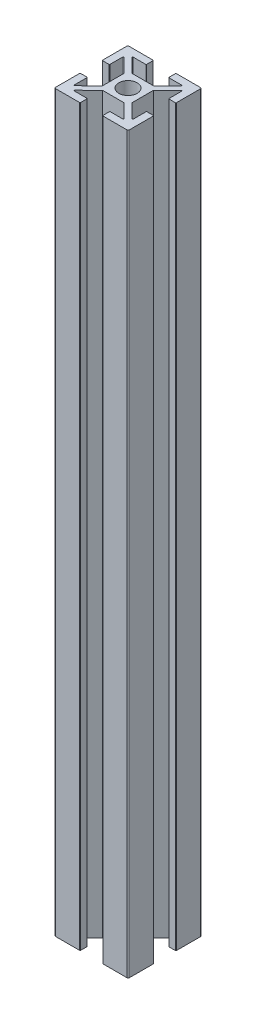
SolidWorks part; units mm, degrees
ref_plane "Front Plane" through (0, 0, 0) normal (0, 0, 1) x (1, 0, 0)
ref_plane "Top Plane" through (0, 0, 0) normal (0, 1, 0) x (1, 0, 0)
ref_plane "Right Plane" through (0, 0, 0) normal (1, 0, 0) x (0, 0, -1)
sketch "Sketch1" plane through (0, 0, 0) normal (0, 1, 0) x (1, 0, 0)
  line L0 (-9.8963, 3) -> (-8.1963, 3)
  line L3 (-3.1963, 10) -> (-9.6963, 10)
  line L4 (-10.0463, 3.15) -> (-10.0463, 9.65)
  line L7 (2.9332, 4) -> (-2.9332, 4)
  line L8 (-4, -2.9454) -> (-4, 2.9454)
  line L9 (-8.0463, 3.15) -> (-8.0463, 6.5862)
  line L10 (-6.6144, 8) -> (-3.1963, 8)
  line L11 (-3.0463, 8.15) -> (-3.0463, 9.85)
  line L12 (-8.0463, 8) -> (-4, 4) construction
  line L13 (-7.7908, 6.6929) -> (-4, 2.9454)
  line L14 (-6.7198, 7.7433) -> (-2.9332, 4)
  line L15 (8.0463, 8) -> (4, 4) construction
  line L22 (0, 0) -> (0, 11.6886) construction
  line L25 (0, 0) -> (-14.9841, 0) construction
  line L27 (6.7198, 7.7433) -> (2.9332, 4)
  line L28 (7.7908, 6.6929) -> (4, 2.9454)
  line L46 (3.0463, 8.15) -> (3.0463, 9.85)
  line L47 (6.6144, 8) -> (3.1963, 8)
  line L48 (8.0463, 3.15) -> (8.0463, 6.5862)
  line L49 (4, -2.9454) -> (4, 2.9454)
  line L50 (10.0463, 3.15) -> (10.0463, 9.65)
  line L51 (3.1963, 10) -> (9.6963, 10)
  line L52 (9.8963, 3) -> (8.1963, 3)
  line L53 (8.0463, -8) -> (4, -4) construction
  line L54 (-8.0463, -8) -> (-4, -4) construction
  line L55 (9.8963, -3) -> (8.1963, -3)
  line L56 (3.1963, -10) -> (9.6963, -10)
  line L57 (10.0463, -3.15) -> (10.0463, -9.65)
  line L58 (8.0463, -3.15) -> (8.0463, -6.5862)
  line L59 (6.6144, -8) -> (3.1963, -8)
  line L60 (3.0463, -8.15) -> (3.0463, -9.85)
  line L61 (7.7908, -6.6929) -> (4, -2.9454)
  line L62 (6.7198, -7.7433) -> (2.9332, -4)
  line L63 (-6.7198, -7.7433) -> (-2.9332, -4)
  line L64 (-7.7908, -6.6929) -> (-4, -2.9454)
  line L65 (-3.0463, -8.15) -> (-3.0463, -9.85)
  line L66 (-6.6144, -8) -> (-3.1963, -8)
  line L67 (-8.0463, -3.15) -> (-8.0463, -6.5862)
  line L68 (2.9332, -4) -> (-2.9332, -4)
  line L69 (-10.0463, -3.15) -> (-10.0463, -9.65)
  line L70 (-3.1963, -10) -> (-9.6963, -10)
  line L71 (-9.8963, -3) -> (-8.1963, -3)
  circle A0 centre (0, 0) radius 2.5
  arc A1 (-10.0463, 9.65) -> (-9.6963, 10) centre (-9.6963, 9.65) cw
  arc A2 (-9.8963, 3) -> (-10.0463, 3.15) centre (-9.8963, 3.15) cw
  arc A3 (-8.1963, 3) -> (-8.0463, 3.15) centre (-8.1963, 3.15) ccw
  arc A4 (-3.1963, 10) -> (-3.0463, 9.85) centre (-3.1963, 9.85) cw
  arc A5 (-3.1963, 8) -> (-3.0463, 8.15) centre (-3.1963, 8.15) ccw
  arc A6 (-6.7198, 7.7433) -> (-6.6144, 8) centre (-6.6144, 7.85) cw
  arc A7 (-7.7908, 6.6929) -> (-8.0463, 6.5862) centre (-7.8963, 6.5862) ccw
  arc A8 (7.7908, 6.6929) -> (8.0463, 6.5862) centre (7.8963, 6.5862) cw
  arc A9 (6.7198, 7.7433) -> (6.6144, 8) centre (6.6144, 7.85) ccw
  arc A10 (3.1963, 8) -> (3.0463, 8.15) centre (3.1963, 8.15) cw
  arc A11 (3.1963, 10) -> (3.0463, 9.85) centre (3.1963, 9.85) ccw
  arc A12 (8.1963, 3) -> (8.0463, 3.15) centre (8.1963, 3.15) cw
  arc A13 (9.8963, 3) -> (10.0463, 3.15) centre (9.8963, 3.15) ccw
  arc A14 (10.0463, 9.65) -> (9.6963, 10) centre (9.6963, 9.65) ccw
  arc A15 (10.0463, -9.65) -> (9.6963, -10) centre (9.6963, -9.65) cw
  arc A16 (9.8963, -3) -> (10.0463, -3.15) centre (9.8963, -3.15) cw
  arc A17 (8.1963, -3) -> (8.0463, -3.15) centre (8.1963, -3.15) ccw
  arc A18 (3.1963, -10) -> (3.0463, -9.85) centre (3.1963, -9.85) cw
  arc A19 (3.1963, -8) -> (3.0463, -8.15) centre (3.1963, -8.15) ccw
  arc A20 (6.7198, -7.7433) -> (6.6144, -8) centre (6.6144, -7.85) cw
  arc A21 (7.7908, -6.6929) -> (8.0463, -6.5862) centre (7.8963, -6.5862) ccw
  arc A22 (-7.7908, -6.6929) -> (-8.0463, -6.5862) centre (-7.8963, -6.5862) cw
  arc A23 (-6.7198, -7.7433) -> (-6.6144, -8) centre (-6.6144, -7.85) ccw
  arc A24 (-3.1963, -8) -> (-3.0463, -8.15) centre (-3.1963, -8.15) cw
  arc A25 (-3.1963, -10) -> (-3.0463, -9.85) centre (-3.1963, -9.85) ccw
  arc A26 (-8.1963, -3) -> (-8.0463, -3.15) centre (-8.1963, -3.15) cw
  arc A27 (-9.8963, -3) -> (-10.0463, -3.15) centre (-9.8963, -3.15) ccw
  arc A28 (-10.0463, -9.65) -> (-9.6963, -10) centre (-9.6963, -9.65) ccw
  point P8 (-10.0463, 10)
  point P27 (-10.0463, 3)
  point P30 (3.0463, 8)
  point P31 (10.0463, -10)
  point P50 (4, 0)
  point P55 (-8.0463, 3)
  point P58 (-3.0463, 10)
  point P61 (-3.0463, 8)
  point P63 (0, 4)
  point P65 (3.0463, 10)
  point P66 (8.0463, 3)
  point P67 (10.0463, 3)
  point P68 (10.0463, 10)
  point P118 (-4, 0)
  point P119 (10.0463, -3)
  point P120 (8.0463, -3)
  point P121 (3.0463, -10)
  point P122 (0, -4)
  point P123 (-3.0463, -8)
  point P124 (-3.0463, -10)
  point P125 (-8.0463, -3)
  point P126 (3.0463, -8)
  point P127 (-10.0463, -3)
  point P128 (-10.0463, -10)
  dimension "D2" = 0.35
  dimension "D3" = 0.15
  dimension "D4" = 0.15
  dimension "D5" = 0.15
  dimension "D12" = 0.15
  dimension "D13" = 0.15
  dimension "D14" = 0.15
  dimension "D6" = 2
  dimension "D7" = 7
  dimension "D8" = 7
  dimension "D9" = 2
  dimension "D10" = 0.75
  dimension "D11" = 0.75
extrude "Boss-Extrude2" add sketch "Sketch1" along normal blind 200
